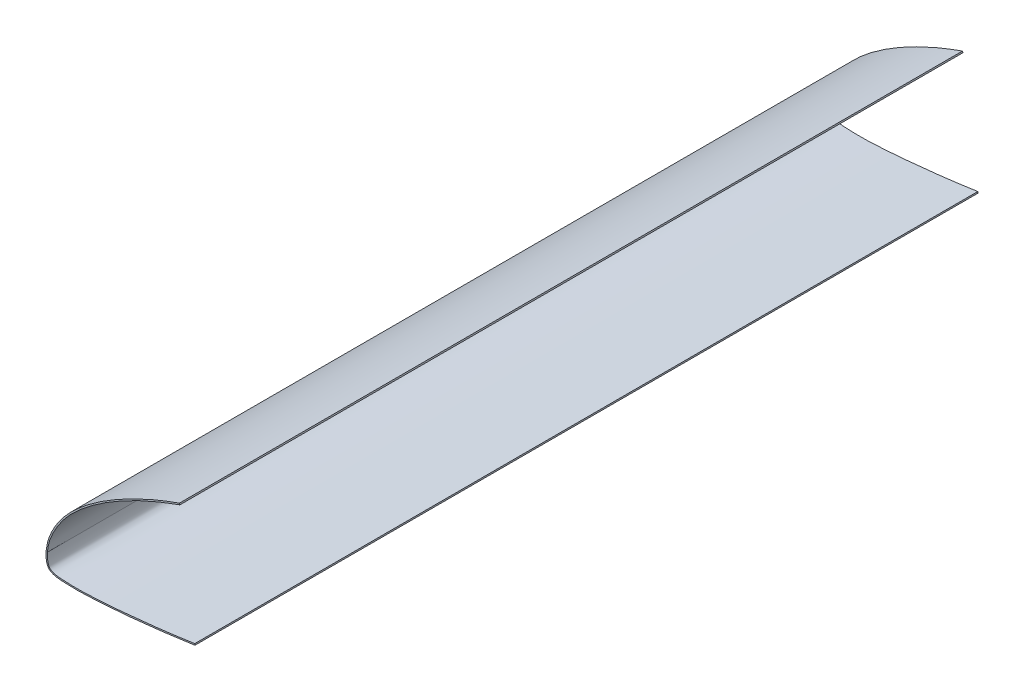
SolidWorks part; units mm, degrees
material "Balsa"
ref_plane "Front Plane" through (0, 0, 0) normal (0, 0, 1) x (1, 0, 0)
ref_plane "Top Plane" through (0, 0, 0) normal (0, 1, 0) x (1, 0, 0)
ref_plane "Right Plane" through (0, 0, 0) normal (1, 0, 0) x (0, 0, -1)
sketch "Sketch1" plane through (0, 0, 319.6812) normal (0, 0, -1) x (-1, 0, 0)
  line L0 (-184.8076, 344.2228) -> (-184.9276, 343.4382)
  line L1 (-176.1168, 410.0281) -> (-175.8536, 410.7769)
  spline S0 degree 3 poles (-564.2922, 1269.4208) (-457.6598, 430.6577) (-316.14, 359.9559) (-161.4648, 341.116) (-151.7076, 340.0565) (-143.8933, 339.3043) (-138.0293, 338.7989) (-132.161, 338.3633) (-126.2868, 338.0034) (-120.4106, 337.71) (-114.5633, 337.625) (-109.6556, 337.8109) (-105.7718, 337.9706) (-103.0113, 338.411) (-100.801, 339.3717) (-99.7769, 340.5107) (-99.2564, 341.6989) (-98.9483, 343.0926) (-98.7918, 344.5081) (-97.9917, 366.4941) (-116.1312, 400.4481) (619.7643, -347.9648) knots -0.702753 -0.702753 -0.702753 -0.702753 0.019248 0.038407 0.057567 0.067147 0.076727 0.086307 0.095887 0.105466 0.115046 0.124626 0.129416 0.134206 0.138996 0.141391 0.143786 0.146181 0.148576 0.150971 0.257462 0.257462 0.257462 0.257462 only from (-184.8076, 344.2228) to (-98.7438, 347.3803) construction
  spline S1 degree 3 poles (666.4874, 991.1276) (-121.3547, 273.4675) (-93.0368, 324.6577) (-99.9174, 353.6847) (-101.056, 356.6902) (-102.8871, 360.5956) (-105.6278, 365.23) (-109.554, 370.3861) (-114.0071, 375.103) (-120.469, 380.8792) (-129.1947, 387.3737) (-140.3145, 394.2034) (-340.8023, 498.0969) (-690.5005, 288.3811) (552.1254, 1095.3464) knots 0.706317 0.706317 0.706317 0.706317 0.841369 0.846483 0.851598 0.856712 0.866941 0.87717 0.887399 0.897628 0.918086 0.938543 0.959001 1.979132 1.979132 1.979132 1.979132 only from (-98.7438, 347.3803) to (-176.1168, 410.0281) construction
  spline S2 degree 3 poles (-184.8076, 344.2228) (-180.9288, 343.6297) (-173.1581, 342.5403) (-161.4648, 341.116) (-151.7076, 340.0565) (-143.8933, 339.3043) (-138.0293, 338.7989) (-132.161, 338.3633) (-126.2868, 338.0034) (-120.4106, 337.71) (-114.5633, 337.625) (-109.6556, 337.8109) (-105.7718, 337.9706) (-103.0113, 338.411) (-100.801, 339.3717) (-99.7769, 340.5107) (-99.2564, 341.6989) (-98.9483, 343.0926) (-98.7918, 344.5081) (-98.7401, 345.9276) (-98.7423, 346.8981) (-98.7438, 347.3803) knots 0.000088 0.000088 0.000088 0.000088 0.019248 0.038407 0.057567 0.067147 0.076727 0.086307 0.095887 0.105466 0.115046 0.124626 0.129416 0.134206 0.138996 0.141391 0.143786 0.146181 0.148576 0.150971 0.153366 0.153366 0.153366 0.153366
  spline S3 degree 3 poles (-98.7438, 347.3803) (-98.8924, 348.4519) (-99.1907, 350.6191) (-99.9174, 353.6847) (-101.056, 356.6902) (-102.8871, 360.5956) (-105.6278, 365.23) (-109.554, 370.3861) (-114.0071, 375.103) (-120.469, 380.8792) (-129.1947, 387.3737) (-140.3145, 394.2034) (-155.7767, 402.216) (-167.9058, 407.1415) (-176.1168, 410.0281) knots 0.836254 0.836254 0.836254 0.836254 0.841369 0.846483 0.851598 0.856712 0.866941 0.87717 0.887399 0.897628 0.918086 0.938543 0.959001 0.999917 0.999917 0.999917 0.999917
  spline S4 degree 1 poles (-184.9276, 343.4382) (-97.9502, 347.4363) knots 0 0 1 1 construction
  spline S5 degree 1 poles (-97.9502, 347.4363) (-175.8536, 410.7769) knots 0 0 1 1 construction
  spline S6 degree 3 poles (-184.9276, 343.4382) (-181.0409, 342.8439) (-173.2531, 341.7521) (-161.5421, 340.3259) (-151.7702, 339.2649) (-143.9419, 338.5116) (-138.0659, 338.0055) (-132.1836, 337.5693) (-126.2983, 337.209) (-120.4024, 336.9152) (-115.4947, 336.8453) (-111.5468, 336.9448) (-108.6148, 337.0592) (-105.6686, 337.1808) (-103.2377, 337.5717) (-101.3131, 338.2815) (-100.0178, 339.0422) (-99.0569, 340.137) (-98.4774, 341.5212) (-98.1545, 343.0219) (-97.9427, 345.0016) (-97.9472, 346.4585) (-97.9502, 347.4363) knots 0.000088 0.000088 0.000088 0.000088 0.019259 0.038429 0.0576 0.067186 0.076771 0.086357 0.095942 0.105527 0.115113 0.119906 0.124698 0.129491 0.134284 0.13668 0.139076 0.141473 0.143869 0.146265 0.148662 0.153454 0.153454 0.153454 0.153454
  spline S7 degree 3 poles (-97.9502, 347.4363) (-98.1006, 348.5203) (-98.3972, 350.6954) (-99.1426, 353.8753) (-100.3069, 356.9593) (-102.1642, 360.9296) (-104.9439, 365.6392) (-108.9224, 370.8712) (-113.4287, 375.6493) (-119.9474, 381.4801) (-128.7284, 388.018) (-139.9073, 394.8861) (-155.44, 402.9365) (-167.6111, 407.8793) (-175.8536, 410.7769) knots 0.83617 0.83617 0.83617 0.83617 0.841287 0.846404 0.851521 0.856638 0.866872 0.877107 0.887341 0.897575 0.918043 0.938512 0.95898 0.999917 0.999917 0.999917 0.999917
  dimension "D1" = 0.7937
extrude "Boss-Extrude1" add sketch "Sketch1" against normal up to vertex (457.2 mm away)
